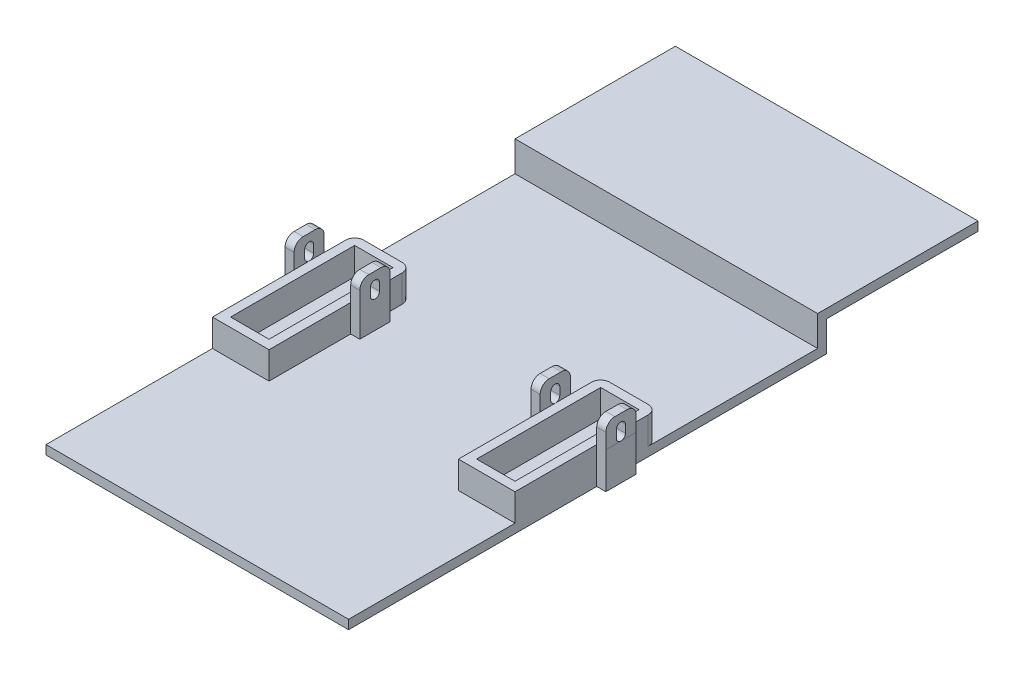
SolidWorks part; units mm, degrees
ref_plane "Plano frontal" through (0, 0, 0) normal (0, 0, 1) x (1, 0, 0)
ref_plane "Plano superior" through (0, 0, 0) normal (0, 1, 0) x (1, 0, 0)
ref_plane "Plano direito" through (0, 0, 0) normal (1, 0, 0) x (0, 0, -1)
sketch "Esboço1" plane through (0, 0, 0) normal (0, 1, 0) x (1, 0, 0)
  line L1 (-50, 50) -> (50, 50)
  line L2 (-50, 50) -> (-50, -50)
  line L3 (-50, -50) -> (50, -50)
  line L4 (50, 50) -> (50, -50)
  line L5 (-50, 50) -> (50, -50) construction
  line L6 (-50, -50) -> (50, 50) construction
  point P0 (0, 0)
  dimension "D1" = 100
  dimension "D2" = 100
extrude "Extrusão1" add sketch "Esboço1" along normal blind 3
sketch "Esboço2" plane through (0, 3, 0) normal (0, 1, 0) x (1, 0, 0)
  line L0 (-50, -3) -> (-31.3, -3)
  line L1 (-50, 50) -> (-50, -50) construction
  line L2 (-31.3, -3) -> (-31.3, -50)
  line L3 (-50, -50) -> (50, -50) construction
  line L4 (-31.3, -50) -> (-31.3, -3)
  line L5 (-50, -23) -> (-53, -23)
  line L6 (-53, -23) -> (-53, -13)
  line L7 (-53, -13) -> (-50, -13)
  line L8 (-50, -13) -> (-31.3, -13)
  line L12 (-50, -3) -> (-50, -13)
  line L13 (-31.3, -50) -> (-50, -50)
  line L14 (-50, -50) -> (-50, -23)
  dimension "D1" = 47
  dimension "D2" = 18.7
  dimension "D3" = 27
  dimension "D4" = 10
  dimension "D5" = 3
extrude "Extrusão2" add sketch "Esboço2" along normal blind 9 contours L13 L2 L0 L12 L7 L6 L5 L14
sketch "Esboço3" plane through (0, 12, 0) normal (0, 1, 0) x (-1, 0, 0)
  line L0 (50, 3) -> (31.3, 3) construction
  line L1 (47, 6) -> (34.3, 6)
  line L2 (47, 6) -> (47, 47)
  line L3 (47, 47) -> (34.3, 47)
  line L4 (34.3, 6) -> (34.3, 47)
  line L5 (47, 6) -> (34.3, 47) construction
  line L6 (47, 47) -> (34.3, 6) construction
  line L7 (31.3, 50) -> (50, 50) construction
  line L8 (31.3, 3) -> (31.3, 50) construction
  line L9 (50, 3) -> (50, 13) construction
  point P0 (40.65, 26.5)
  dimension "D1" = 3
  dimension "D2" = 3
  dimension "D3" = 3
  dimension "D4" = 3
extrude "Extrusão3" cut sketch "Esboço3" against normal blind 9
ref_plane "Plano1" through (-53, 3, 13) normal (0, 0, -1) x (-1, 0, 0)
fillet "Filete2" radius 3 2 edges at (-31.3, 7.5, 3)
sketch "Esboço6" plane through (0, 3, 0) normal (0, -1, 0) x (1, 0, 0)
  line L0 (-53, 23) -> (-50, 23)
  line L1 (-50, 23) -> (-50, 13)
  line L2 (-50, 13) -> (-53, 13)
  line L3 (-53, 13) -> (-53, 23)
extrude "Extrusão4" add sketch "Esboço6" along normal blind 3
sketch "Esboço7" plane through (0, 3, 0) normal (0, 1, 0) x (1, 0, 0)
  line L0 (-31.3, -13) -> (-28.3, -13)
  line L1 (-31.3, -50) -> (50, -50) construction
  line L3 (-28.3, -13) -> (-28.3, -23)
  line L4 (-28.3, -23) -> (-31.3, -23)
  line L5 (-31.3, -13) -> (-31.3, -23)
  dimension "D1" = 3
  dimension "D2" = 10
  dimension "D3" = 27
extrude "Extrusão5" add sketch "Esboço7" along normal blind 17
sketch "Esboço8" plane through (0, 12, 0) normal (0, 1, 0) x (1, 0, 0)
  line L0 (-53.0004, -13) -> (-50.0534, -13)
  line L1 (-50.25, -13) -> (-55.75, -13) construction
  line L2 (-50.0534, -13) -> (-50, -23)
  line L3 (-50, -23) -> (-53, -23)
  line L4 (-53, -23) -> (-53.0004, -13)
extrude "Extrusão6" add sketch "Esboço8" along normal blind 8
sketch "Esboço9" plane through (-28.3, 0, 0) normal (1, 0, 0) x (0, 0, -1)
  line L1 (-19.5, 16) -> (-19.5, 13.5)
  line L2 (-50, 12) -> (-50, 3) construction
  line L4 (-16.5, 16) -> (-16.5, 13.5)
  arc A0 (-18, 17.5) -> (-19.5, 16) centre (-18, 16) ccw
  arc A1 (-19.5, 13.5) -> (-18, 12) centre (-18, 13.5) ccw
  arc A2 (-16.5, 16) -> (-19.5, 16) centre (-18, 16) ccw
  arc A3 (-19.5, 13.5) -> (-16.5, 13.5) centre (-18, 13.5) ccw
  point P0 (-23, 14.75)
  point P11 (-24.5, 17.5)
  dimension "D4" = 1.5
  dimension "D5" = 1.5
  dimension "D1" = 30.5
fillet "Filete3" radius 3 4 edges at (-29.8, 20, 13) (-51.5269, 20, 13) (-29.8, 20, 23) (-51.5, 20, 23)
mirror "Espelhar4" about plane through (0, 0, 0) normal (1, 0, 0) of "Extrusão1", "Filete2", "Extrusão6", "Extrusão5", "Extrusão4", "Extrusão3", "Extrusão2", "Filete3"
extrude "Extrusão17" cut sketch "Esboço9" against normal blind 10 contours A1 A3 L4 A2 A0 L1
sketch "Esboço15" plane through (-50.1213, 0, 0.2674) normal (1, 0, -0.0053) x (-0.0053, 0, -1)
  line L2 (-19.2329, 16.01) -> (-19.2329, 13.51)
  line L4 (-16.2329, 16.01) -> (-16.2329, 13.51)
  line L9 (-22.7329, 17) -> (-22.7329, 12) construction
  arc A0 (-17.7329, 17.51) -> (-16.2329, 16.01) centre (-17.7329, 16.01) cw
  arc A1 (-19.2329, 13.51) -> (-17.7329, 12.01) centre (-17.7329, 13.51) ccw
  arc A2 (-16.2329, 16.01) -> (-19.2329, 16.01) centre (-17.7329, 16.01) ccw
  arc A3 (-19.2329, 16.01) -> (-17.7329, 17.51) centre (-17.7329, 16.01) cw
  arc A4 (-19.2329, 13.51) -> (-16.2329, 13.51) centre (-17.7329, 13.51) ccw
  arc A5 (-16.2329, 13.51) -> (-17.7329, 12.01) centre (-17.7329, 13.51) cw
  point P0 (-17.7329, 14.76)
  dimension "D5" = 1.5
  dimension "D6" = 1.5
  dimension "D4" = 5
extrude "Extrusão30" cut sketch "Esboço15" against normal blind 10 contours A2 L4 A4 L2
mirror "Espelhar14" about plane through (0, 0, 0) normal (1, 0, 0) of "Extrusão17", "Extrusão30"
sketch "Esboço22" plane through (0, 0, -50) normal (0, 0, -1) x (-1, 0, 0)
  line L1 (50, 3) -> (-50, 3)
  line L2 (50, 3) -> (50, 0)
  line L3 (50, 0) -> (-50, 0)
  line L4 (-50, 3) -> (-50, 0)
extrude "Extrusão33" add sketch "Esboço22" along normal blind 53
sketch "Esboço23" plane through (0, 3, 0) normal (0, 1, 0) x (1, 0, 0)
  line L0 (50, -6) -> (50, 103) construction
  line L1 (-50, 103) -> (50, 103)
  line L2 (-50, 103) -> (-50, 50)
  line L3 (-50, 50) -> (50, 50)
  line L4 (50, 103) -> (50, 50)
  dimension "D1" = 53
extrude "Extrusão35" add sketch "Esboço23" along normal blind 10
sketch "Esboço24" plane through (50, 0, 0) normal (1, 0, 0) x (0, 0, -1)
  line L0 (50, 13) -> (103, 13) construction
  line L1 (103, 0) -> (53, 0)
  line L2 (103, 0) -> (103, 10)
  line L3 (103, 10) -> (53, 10)
  line L4 (53, 0) -> (53, 10)
  dimension "D1" = 50
  dimension "D2" = 3
extrude "Extrusão36" cut sketch "Esboço24" against normal through all
sketch "Esboço26" plane through (0, 0, 50) normal (0, 0, 1) x (1, 0, 0)
  line L0 (-31.3, 3) -> (-50, 3)
  line L1 (-50, 12) -> (-50, 0) construction
  line L2 (-50, 3) -> (-50, 0)
  line L3 (-50, 0) -> (50, 0)
  line L4 (50, 0) -> (50, 3)
  line L5 (50, 12) -> (50, 0) construction
  line L6 (50, 3) -> (-50, 3)
  line M1 (-50, 12) -> (-50, 0)
  line M2 (-50, 0) -> (50, 0)
  line M3 (50, 0) -> (50, 12)
  line M6 (31.3, 3) -> (-31.3, 3)
extrude "Ressalto-extrusão1" add sketch "Esboço26" along normal blind 55 contours L6 L0 M3 M6 M1 M2
